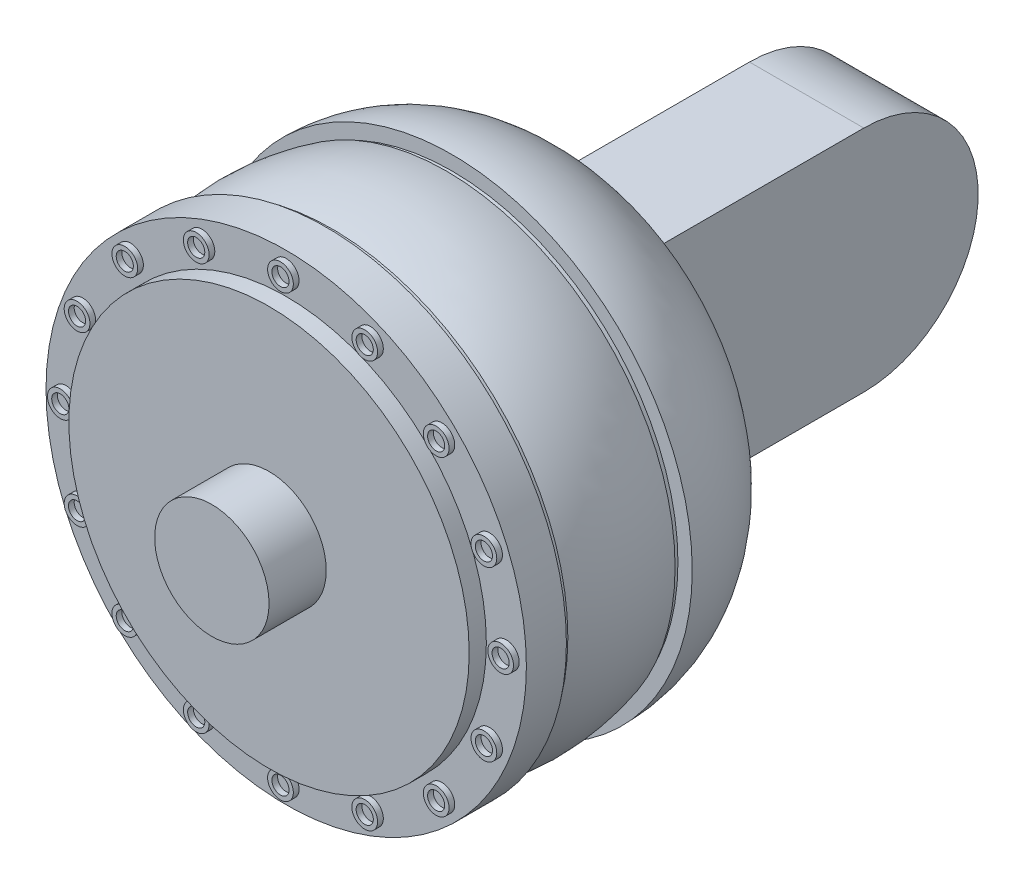
SolidWorks part; units mm, degrees
ref_plane "Front Plane" through (0, 0, 0) normal (0, 0, 1) x (1, 0, 0)
ref_plane "Top Plane" through (0, 0, 0) normal (0, 1, 0) x (1, 0, 0)
ref_plane "Right Plane" through (0, 0, 0) normal (1, 0, 0) x (0, 0, -1)
sketch "Sketch1" plane through (0, 0, 0) normal (0, 1, 0) x (1, 0, 0)
  line L0 (0, 0) -> (0, -20)
  line L1 (0, -20) -> (-42, -20)
  line L2 (-32, 0) -> (0, 0)
  arc A0 (-42, -20) -> (-32, 0) centre (-17, -20) cw
  dimension "D3" = 25
  dimension "D1" = 20
  dimension "D2" = 42
revolve "Revolve1" add sketch "Sketch1" angle 360 about L0
sketch "Sketch2" plane through (0, 0, 20) normal (0, 0, 1) x (1, 0, 0)
  circle A0 centre (0, 0) radius 39.5
  dimension "D1" = 79
extrude "Boss-Extrude1" add sketch "Sketch2" along normal blind 1
sketch "Sketch3" plane through (0, 0, 0) normal (0, 1, 0) x (1, 0, 0)
  line L0 (0, -21) -> (-40, -21)
  line L1 (-39.5, -21) -> (39.5, -21) construction
  line L2 (0, -21) -> (0, -41)
  line L3 (0, -41) -> (-40, -41)
  arc A1 (-40, -41) -> (-40, -21) centre (-4.377, -31) cw
  dimension "D3" = 37
  dimension "D1" = 40
  dimension "D2" = 20
revolve "Revolve2" add sketch "Sketch3" angle 360 about L2
sketch "Sketch4" plane through (0, 0, 41) normal (0, 0, 1) x (1, 0, 0)
  circle A0 centre (0, 0) radius 41.25
  dimension "D1" = 82.5
extrude "Boss-Extrude2" add sketch "Sketch4" along normal blind 1
sketch "Sketch5" plane through (0, 0, 42) normal (0, 0, 1) x (1, 0, 0)
  circle A0 centre (0, 0) radius 42
  dimension "D1" = 84
extrude "Boss-Extrude3" add sketch "Sketch5" along normal blind 7
sketch "Sketch6" plane through (0, 0, 49) normal (0, 0, 1) x (1, 0, 0)
  circle A0 centre (0, 0) radius 35
  dimension "D1" = 70
extrude "Boss-Extrude4" add sketch "Sketch6" along normal blind 3
sketch "Sketch7" plane through (0, 0, 49) normal (0, 0, 1) x (1, 0, 0)
  circle A3 centre (38.5, 0) radius 2.25
  circle A4 centre (38.5, 0) radius 1.5
  dimension "D1" = 4.5
  dimension "D2" = 3
extrude "Boss-Extrude5" add sketch "Sketch7" along normal blind 1
pattern_circular "CirPattern1" count 16 over 360 about axis through (0, 0, 0) along (0, 0, 1) of "Boss-Extrude5"
sketch "Sketch8" plane through (0, 0, 0) normal (0, 0, -1) x (-1, 0, 0)
  line L1 (-10, 20) -> (10, 20)
  line L2 (-10, 20) -> (-10, -20)
  line L3 (-10, -20) -> (10, -20)
  line L4 (10, 20) -> (10, -20)
  line L5 (-10, 20) -> (10, -20) construction
  line L6 (-10, -20) -> (10, 20) construction
  point P0 (0, 0)
  dimension "D1" = 40
  dimension "D2" = 20
extrude "Boss-Extrude6" add sketch "Sketch8" along normal blind 42
sketch "Sketch9" plane through (-10, 0, 0) normal (-1, 0, 0) x (0, 0, 1)
  line L0 (-42, -20) -> (-42, 20) construction
  circle A0 centre (-42, 0) radius 20
extrude "Boss-Extrude7" add sketch "Sketch9" against normal up to surface (20 mm away) up to face at (10, 0, -21)
sketch "Sketch10" plane through (-10, 0, 0) normal (-1, 0, 0) x (0, 0, 1)
  circle A0 centre (-42, 0) radius 10
  dimension "D1" = 20
extrude "Boss-Extrude8" add sketch "Sketch10" along normal blind 10
sketch "Sketch11" plane through (0, 0, 52) normal (0, 0, 1) x (1, 0, 0)
  circle A0 centre (0, 0) radius 10
  dimension "D1" = 20
extrude "Boss-Extrude9" add sketch "Sketch11" along normal blind 10
